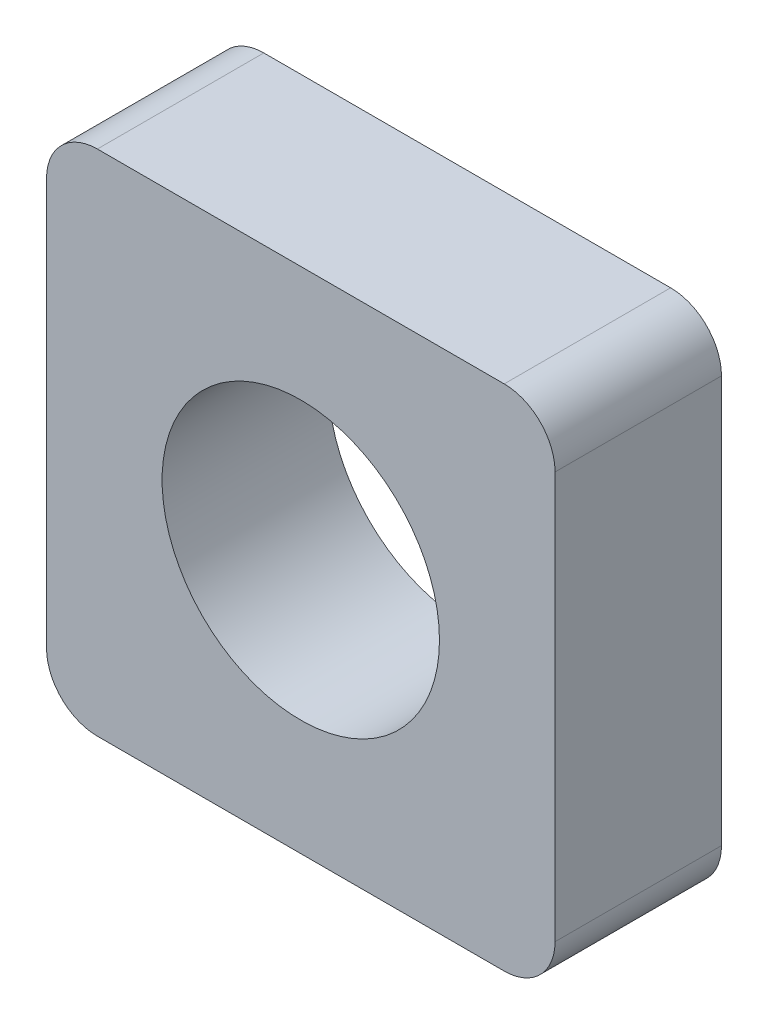
SolidWorks part; units mm, degrees
material "Cast Stainless Steel"
ref_plane "Front Plane" through (0, 0, 0) normal (0, 0, 1) x (1, 0, 0)
ref_plane "Top Plane" through (0, 0, 0) normal (0, 1, 0) x (1, 0, 0)
ref_plane "Right Plane" through (0, 0, 0) normal (1, 0, 0) x (0, 0, -1)
sketch "Sketch1" plane through (0, 0, 0) normal (0, 0, 1) x (1, 0, 0)
  line L1 (-2.75, 2.75) -> (2.75, 2.75)
  line L2 (-2.75, 2.75) -> (-2.75, -2.75)
  line L3 (-2.75, -2.75) -> (2.75, -2.75)
  line L4 (2.75, 2.75) -> (2.75, -2.75)
  line L5 (-2.75, 2.75) -> (2.75, -2.75) construction
  line L6 (-2.75, -2.75) -> (2.75, 2.75) construction
  circle A0 centre (0, 0) radius 1.5
  dimension "D2" = 3
  dimension "D1" = 5.5
extrude "Boss-Extrude1" add sketch "Sketch1" along normal blind 1.8
fillet "Fillet1" radius 0.55 4 edges at (-2.75, -2.75, 0.9) (2.75, -2.75, 0.9) (-2.75, 2.75, 0.9) (2.75, 2.75, 0.9)
equation "\"d\"= 3"
equation "\"m\"= 1.8"
equation "\"S\"= 5.5"
equation "\"D1@Sketch1\"=\"S\""
equation "\"D2@Sketch1\"=\"d\""
equation "\"D1@Boss-Extrude1\"=\"m\""
equation "\"D1@Fillet1\"=\"S\"/10"
